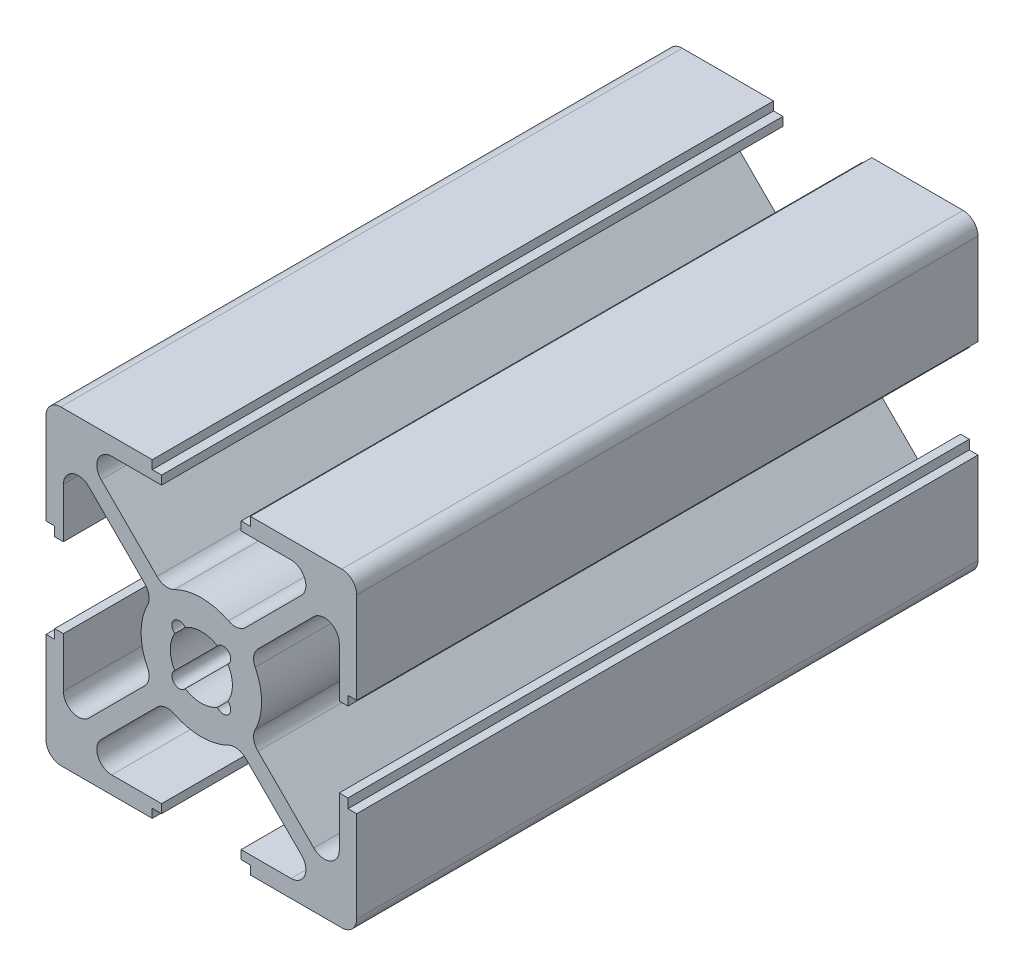
SolidWorks part; units mm, degrees
ref_plane "Ön Düzlem" through (0, 0, 0) normal (0, 0, 1) x (1, 0, 0)
ref_plane "Üst Düzlem" through (0, 0, 0) normal (0, 1, 0) x (1, 0, 0)
ref_plane "Sağ Düzlem" through (0, 0, 0) normal (1, 0, 0) x (0, 0, -1)
sketch "Çizim1" plane through (0, 0, 0) normal (0, 0, 1) x (1, 0, 0)
  line L0 (3.95, 12.5) -> (11.3, 12.5)
  line L1 (-11.3, 12.5) -> (-3.95, 12.5)
  line L2 (-12.5, 11.3) -> (-12.5, 3.95)
  line L3 (-11.3, -12.5) -> (-3.95, -12.5)
  line L4 (12.5, 11.3) -> (12.5, 3.95)
  line L5 (9.0515, 8.0615) -> (4.5565, 3.5666)
  line L6 (8.0615, -9.0515) -> (3.5666, -4.5565)
  line L7 (-7.213, 11.1) -> (-3.2, 11.1)
  line L9 (-7.213, -11.1) -> (-3.2, -11.1)
  line L10 (11.1, 7.213) -> (11.1, 3.2)
  line L11 (9.0515, -8.0615) -> (4.5565, -3.5666)
  line L12 (-9.0515, -8.0615) -> (-4.5565, -3.5666)
  line L14 (11.8, -3.2) -> (11.1, -3.2)
  line L16 (11.1, 3.2) -> (11.8, 3.2)
  line L17 (11.1, -3.2) -> (11.1, -7.213)
  line L18 (12.5, -3.95) -> (12.5, -11.3)
  line L19 (11.8, 3.2) -> (11.8, 3.95)
  line L20 (11.8, 3.95) -> (12.5, 3.95)
  line L21 (11.8, -3.2) -> (11.8, -3.95)
  line L22 (11.8, -3.95) -> (12.5, -3.95)
  line L24 (-3.2, 11.8) -> (-3.2, 11.1)
  line L26 (3.2, 11.1) -> (3.2, 11.8)
  line L28 (3.2, 11.1) -> (7.213, 11.1)
  line L29 (-3.2, 11.8) -> (-3.95, 11.8)
  line L30 (-3.95, 11.8) -> (-3.95, 12.5)
  line L31 (3.2, 11.8) -> (3.95, 11.8)
  line L32 (3.95, 11.8) -> (3.95, 12.5)
  line L33 (-12.5, -3.95) -> (-12.5, -11.3)
  line L34 (-11.1, -3.2) -> (-11.1, -7.213)
  line L35 (3.2, -11.1) -> (3.2, -11.8)
  line L36 (3.2, -11.8) -> (3.95, -11.8)
  line L37 (3.95, -11.8) -> (3.95, -12.5)
  line L38 (-3.95, -11.8) -> (-3.95, -12.5)
  line L39 (-3.2, -11.8) -> (-3.95, -11.8)
  line L40 (-3.2, -11.8) -> (-3.2, -11.1)
  line L41 (3.95, -12.5) -> (11.3, -12.5)
  line L42 (3.2, -11.1) -> (7.213, -11.1)
  line L43 (-11.8, 3.95) -> (-12.5, 3.95)
  line L44 (-11.8, 3.2) -> (-11.8, 3.95)
  line L45 (-11.1, 3.2) -> (-11.8, 3.2)
  line L46 (-11.8, -3.95) -> (-12.5, -3.95)
  line L47 (-11.8, -3.2) -> (-11.8, -3.95)
  line L48 (-11.8, -3.2) -> (-11.1, -3.2)
  line L49 (-11.1, 7.213) -> (-11.1, 3.2)
  line L50 (-8.0615, -9.0515) -> (-3.5666, -4.5565)
  line L51 (8.0615, 9.0515) -> (3.5666, 4.5565)
  line L52 (-8.0615, 9.0515) -> (-3.5666, 4.5565)
  line L53 (-9.0515, 8.0615) -> (-4.5565, 3.5666)
  arc A0 (1.2957, 2.1381) -> (-1.2957, 2.1381) centre (0, 0) ccw
  arc A1 (2.1789, 4.333) -> (-2.1789, 4.333) centre (0, 0) ccw
  arc A2 (4.333, -2.1789) -> (4.333, 2.1789) centre (0, 0) ccw
  arc A3 (-2.1789, -4.333) -> (2.1789, -4.333) centre (0, 0) ccw
  arc A4 (-4.333, 2.1789) -> (-4.333, -2.1789) centre (0, 0) ccw
  arc A5 (-7.213, 11.1) -> (-8.0615, 9.0515) centre (-7.213, 9.9) ccw
  arc A6 (-9.0515, 8.0615) -> (-11.1, 7.213) centre (-9.9, 7.213) ccw
  arc A7 (-4.333, 2.1789) -> (-4.5565, 3.5666) centre (-5.4051, 2.7181) ccw
  arc A8 (-3.5666, 4.5565) -> (-2.1789, 4.333) centre (-2.7181, 5.4051) ccw
  arc A9 (2.1789, 4.333) -> (3.5666, 4.5565) centre (2.7181, 5.4051) ccw
  arc A10 (4.333, 2.1789) -> (4.5565, 3.5666) centre (5.4051, 2.7181) cw
  arc A11 (4.333, -2.1789) -> (4.5565, -3.5666) centre (5.4051, -2.7181) ccw
  arc A12 (3.5666, -4.5565) -> (2.1789, -4.333) centre (2.7181, -5.4051) ccw
  arc A13 (-2.1789, -4.333) -> (-3.5666, -4.5565) centre (-2.7181, -5.4051) ccw
  arc A14 (-4.333, -2.1789) -> (-4.5565, -3.5666) centre (-5.4051, -2.7181) cw
  arc A15 (-11.1, -7.213) -> (-9.0515, -8.0615) centre (-9.9, -7.213) ccw
  arc A16 (-8.0615, -9.0515) -> (-7.213, -11.1) centre (-7.213, -9.9) ccw
  arc A17 (7.213, -11.1) -> (8.0615, -9.0515) centre (7.213, -9.9) ccw
  arc A18 (11.1, -7.213) -> (9.0515, -8.0615) centre (9.9, -7.213) cw
  arc A19 (9.0515, 8.0615) -> (11.1, 7.213) centre (9.9, 7.213) cw
  arc A20 (7.213, 11.1) -> (8.0615, 9.0515) centre (7.213, 9.9) cw
  arc A21 (11.3, 12.5) -> (12.5, 11.3) centre (11.3, 11.3) cw
  arc A22 (12.5, -11.3) -> (11.3, -12.5) centre (11.3, -11.3) cw
  arc A23 (-11.3, -12.5) -> (-12.5, -11.3) centre (-11.3, -11.3) cw
  arc A24 (-12.5, 11.3) -> (-11.3, 12.5) centre (-11.3, 11.3) cw
  arc A25 (2.1381, 1.2957) -> (1.2957, 2.1381) centre (1.7678, 1.7678) ccw
  arc A26 (1.2957, -2.1381) -> (2.1381, -1.2957) centre (1.7678, -1.7678) ccw
  arc A27 (-2.1381, -1.2957) -> (-1.2957, -2.1381) centre (-1.7678, -1.7678) ccw
  arc A28 (-1.2957, 2.1381) -> (-2.1381, 1.2957) centre (-1.7678, 1.7678) ccw
  arc A29 (-2.1381, 1.2957) -> (-2.1381, -1.2957) centre (0, 0) ccw
  arc A30 (-1.2957, -2.1381) -> (1.2957, -2.1381) centre (0, 0) ccw
  arc A31 (2.1381, -1.2957) -> (2.1381, 1.2957) centre (0, 0) ccw
  point P0 (0, 0)
  point P5 (0, 0)
  point P52 (5.055, 6.045)
  point P55 (6.045, -5.055)
  point P61 (-5.055, -6.045)
  point P66 (-6.045, 5.055)
  point P68 (0, 0)
  point P117 (0, 0)
  dimension "D1" = 4
  dimension "D2" = 1.2
  dimension "D3" = 4
extrude "Yükseklik-Ekstrüzyon1" add sketch "Çizim1" along normal blind 50
